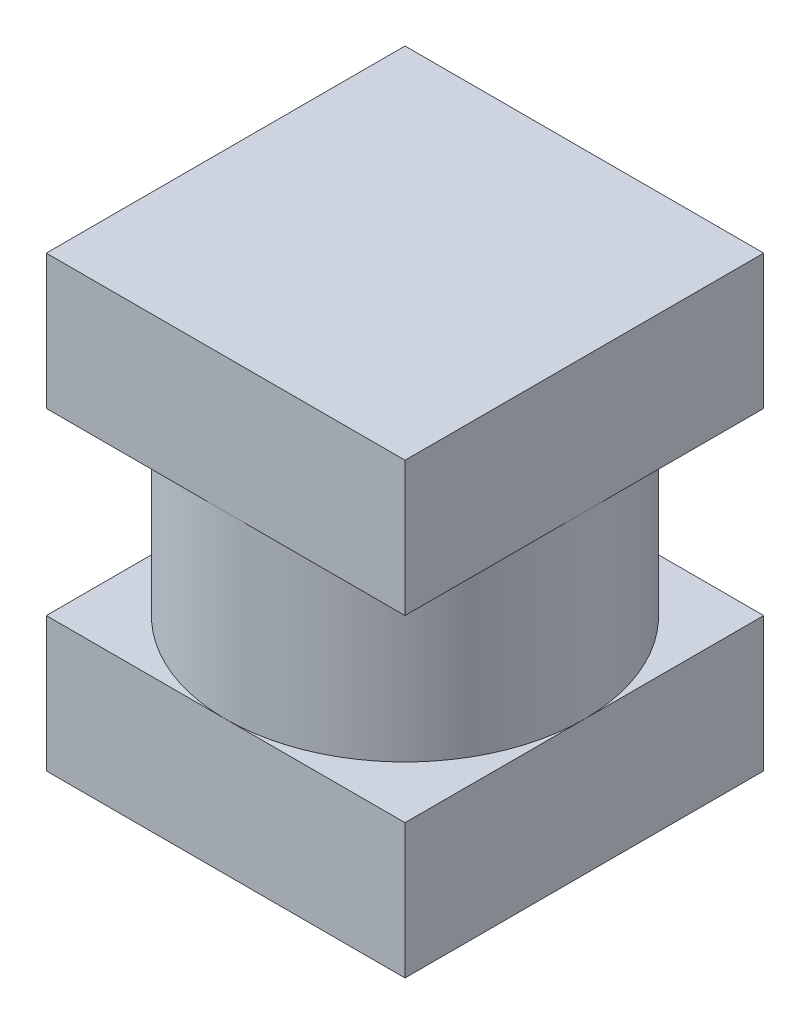
SolidWorks part; units mm, degrees
ref_plane "Front Plane" through (0, 0, 0) normal (0, 0, 1) x (1, 0, 0)
ref_plane "Top Plane" through (0, 0, 0) normal (0, 1, 0) x (1, 0, 0)
ref_plane "Right Plane" through (0, 0, 0) normal (1, 0, 0) x (0, 0, -1)
sketch "Sketch1" plane through (0, 0, 0) normal (0, 1, 0) x (1, 0, 0)
  line L1 (-20, 20) -> (20, 20)
  line L2 (-20, 20) -> (-20, -20)
  line L3 (-20, -20) -> (20, -20)
  line L4 (20, 20) -> (20, -20)
  line L5 (-20, 20) -> (20, -20) construction
  line L6 (-20, -20) -> (20, 20) construction
  point P0 (0, 0)
  dimension "D1" = 40
  dimension "D2" = 40
extrude "Boss-Extrude1" add sketch "Sketch1" along normal blind 15
sketch "Sketch2" plane through (0, 15, 0) normal (0, 1, 0) x (1, 0, 0)
  circle A0 centre (0, 0) radius 20
  dimension "D1" = 40
extrude "Boss-Extrude2" add sketch "Sketch2" along normal blind 20
sketch "Sketch3" plane through (0, 35, 0) normal (0, 1, 0) x (1, 0, 0)
  line L1 (-20, -20) -> (20, -20)
  line L2 (-20, -20) -> (-20, 20)
  line L3 (-20, 20) -> (20, 20)
  line L4 (20, -20) -> (20, 20)
  line L5 (-20, -20) -> (20, 20) construction
  line L6 (-20, 20) -> (20, -20) construction
  point P0 (0, 0)
extrude "Boss-Extrude3" add sketch "Sketch3" along normal blind 15
